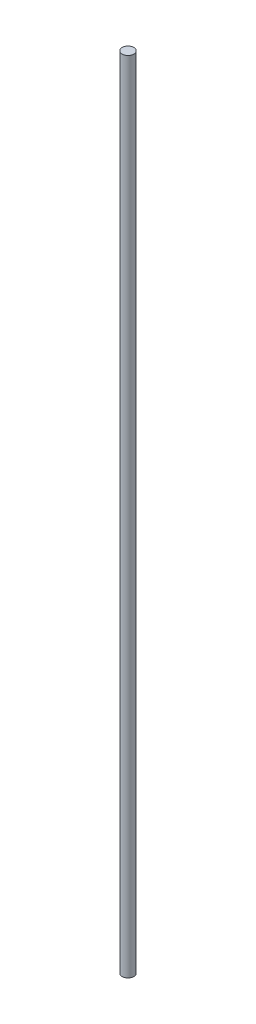
SolidWorks part; units mm, degrees
ref_plane "前视基准面" through (0, 0, 0) normal (0, 0, 1) x (1, 0, 0)
ref_plane "上视基准面" through (0, 0, 0) normal (0, 1, 0) x (1, 0, 0)
ref_plane "右视基准面" through (0, 0, 0) normal (1, 0, 0) x (0, 0, -1)
other "Configuration Table"
sketch "草图1" plane through (0, 0, 0) normal (0, 1, 0) x (1, 0, 0)
  circle A0 centre (0, 0) radius 4
  dimension "D1" = 8
extrude "凸台-拉伸1" add sketch "草图1" along normal blind 550
